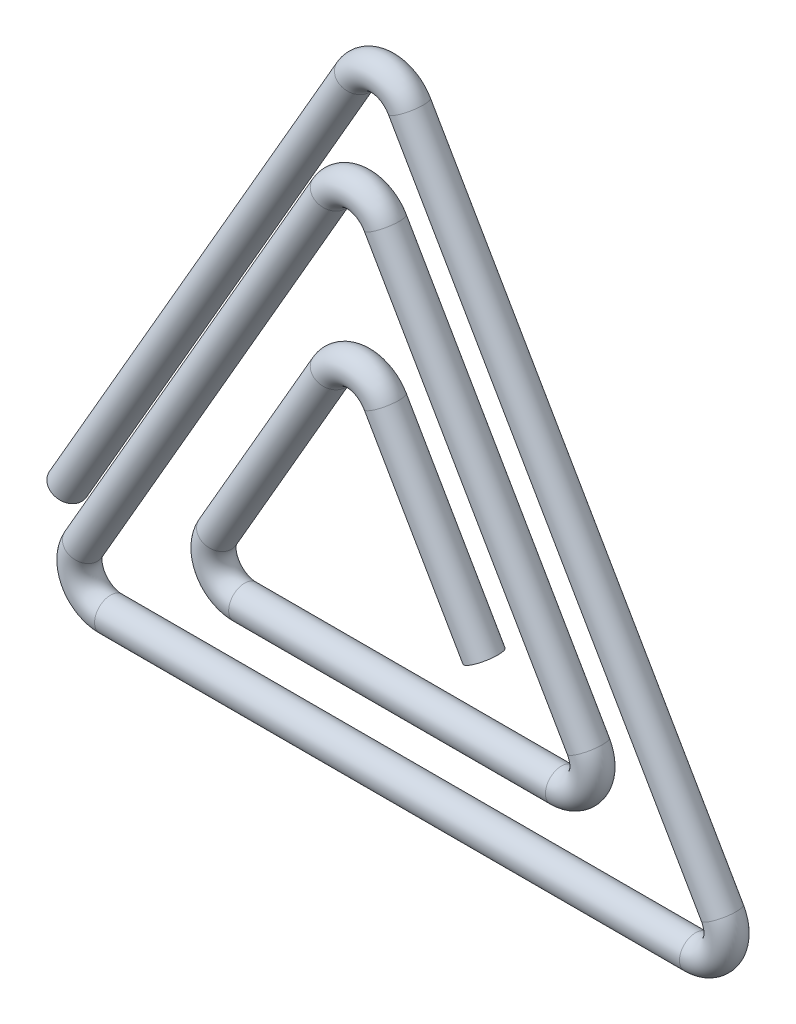
SolidWorks part; units mm, degrees
ref_plane "Спереди" through (0, 0, 0) normal (0, 0, 1) x (1, 0, 0)
ref_plane "Сверху" through (0, 0, 0) normal (0, 1, 0) x (1, 0, 0)
ref_plane "Справа" through (0, 0, 0) normal (1, 0, 0) x (0, 0, -1)
sketch "Эскиз1" plane through (0, 0, 0) normal (0, 0, 1) x (1, 0, 0)
  line L0 (0, 20) -> (17.3205, -10) construction
  line L1 (17.3205, -10) -> (-17.3205, -10) construction
  line L2 (-17.3205, -10) -> (0, 20) construction
  line L3 (0, 36) -> (31.1769, -18) construction
  line L4 (31.1769, -18) -> (-31.1769, -18) construction
  line L5 (-31.1769, -18) -> (0, 36) construction
  line L6 (0, 52) -> (45.0333, -26) construction
  line L7 (45.0333, -26) -> (-45.0333, -26) construction
  line L8 (-45.0333, -26) -> (0, 52) construction
  line L9 (2.5, 47.6699) -> (-30, -8.6218) construction
  line L10 (17.3205, -10) -> (26.5581, -10) construction
  line L11 (31.1769, -18) -> (40.4145, -18) construction
  point P14 (13, -2.5167)
  dimension "D1" = 20
  dimension "D2" = 10
  dimension "D5" = 5
  dimension "D6" = 26
  dimension "D7" = 65
  dimension "D3" = 8
  dimension "D4" = 8
sketch "Эскиз2" plane through (0, 0, 0) normal (0, 0, 1) x (1, 0, 0)
  line L0 (13, -2.5167) -> (2.7857, 15.175)
  line L1 (-2.7857, 15.175) -> (-14.5348, -5.175)
  line L2 (-11.7491, -10) -> (20.9867, -10)
  line L3 (17.3205, -10) -> (-17.3205, -10) construction
  line L4 (23.7724, -5.175) -> (2.7857, 31.175)
  line L5 (-2.7857, 31.175) -> (-28.3912, -13.175)
  line L6 (-25.6055, -18) -> (34.8431, -18)
  line L7 (37.6288, -13.175) -> (5.2857, 42.8449)
  line L8 (-0.2857, 42.8449) -> (-30, -8.6218)
  arc A0 (-0.2857, 42.8449) -> (5.2857, 42.8449) centre (2.5, 41.2366) cw
  arc A1 (37.6288, -13.175) -> (34.8431, -18) centre (34.8431, -14.7834) cw
  arc A2 (-25.6055, -18) -> (-28.3912, -13.175) centre (-25.6055, -14.7834) cw
  arc A3 (-2.7857, 31.175) -> (2.7857, 31.175) centre (0, 29.5667) cw
  arc A4 (23.7724, -5.175) -> (20.9867, -10) centre (20.9867, -6.7834) cw
  arc A5 (-11.7491, -10) -> (-14.5348, -5.175) centre (-11.7491, -6.7834) cw
  arc A6 (-2.7857, 15.175) -> (2.7857, 15.175) centre (0, 13.5667) cw
  point P23 (2.5, 47.6699)
  point P26 (40.4145, -18)
  point P29 (-31.1769, -18)
  point P32 (0, 36)
  point P35 (26.5581, -10)
  point P38 (-17.3205, -10)
  point P41 (0, 20)
  dimension "D1" = 3.2166
ref_plane "Плоскость1" through (13, -2.5167, 0) normal (0.5, -0.866, 0) x (-0.866, -0.5, 0)
sketch "Эскиз3" plane through (13, -2.5167, 0) normal (0.5, -0.866, 0) x (-0.866, -0.5, 0)
  circle A0 centre (0, 0) radius 1.65
  dimension "D1" = 3.3
sweep "По траектории1" add profiles "Эскиз3" path "Эскиз2"
